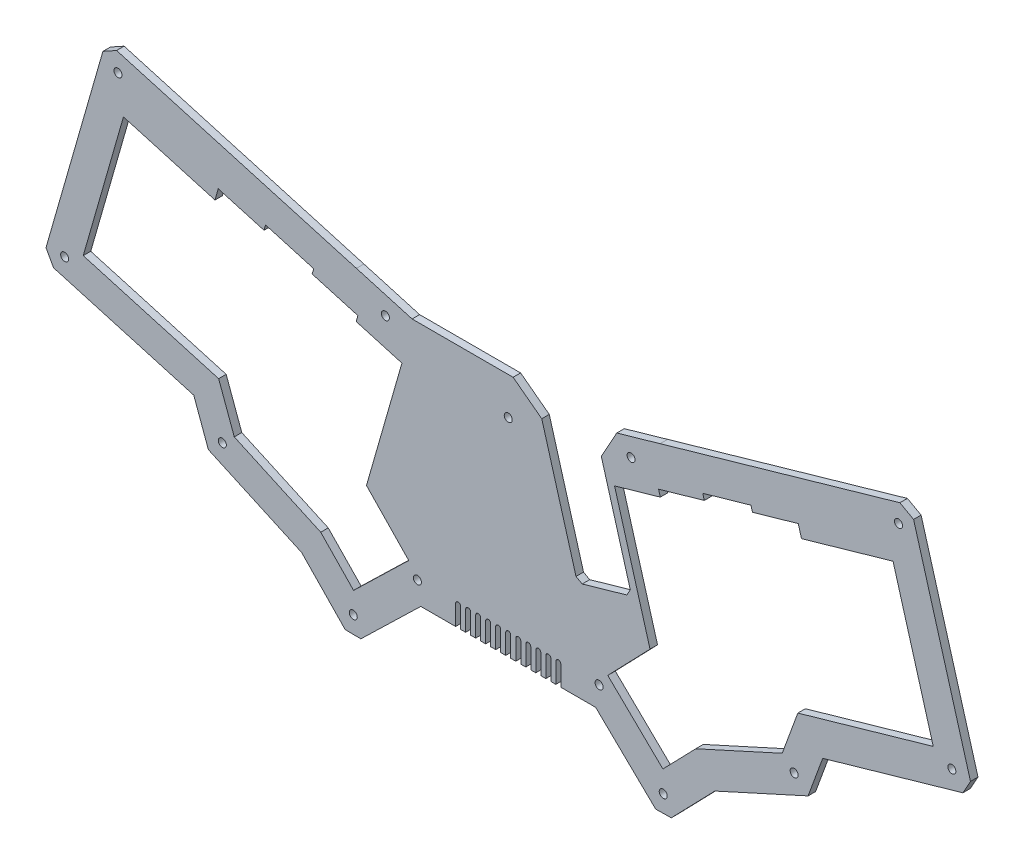
SolidWorks part; units mm, degrees
ref_plane "Plan de face" through (0, 0, 0) normal (0, 0, 1) x (1, 0, 0)
ref_plane "Plan de dessus" through (0, 0, 0) normal (0, 1, 0) x (1, 0, 0)
ref_plane "Plan de droite" through (0, 0, 0) normal (1, 0, 0) x (0, 0, -1)
sketch "Esquisse1" plane through (0, 0, 0) normal (0, 0, 1) x (1, 0, 0)
  line L0 (-121.6461, -32.0475) -> (-108.1875, -28.1884) construction
  line L1 (-108.1875, -28.1884) -> (-104.3283, -41.647) construction
  line L2 (-104.3283, -41.647) -> (-117.7869, -45.5062) construction
  line L3 (-117.7869, -45.5062) -> (-121.6461, -32.0475) construction
  line L4 (-100.1763, -37.9855) -> (-104.0355, -24.5269) construction
  line L5 (-104.0355, -24.5269) -> (-90.5769, -20.6677) construction
  line L6 (-90.5769, -20.6677) -> (-86.7177, -34.1263) construction
  line L7 (-86.7177, -34.1263) -> (-100.1763, -37.9855) construction
  line L8 (-82.5657, -30.4649) -> (-86.4249, -17.0063) construction
  line L9 (-86.4249, -17.0063) -> (-72.9663, -13.1471) construction
  line L10 (-72.9663, -13.1471) -> (-69.1071, -26.6057) construction
  line L11 (-69.1071, -26.6057) -> (-82.5657, -30.4649) construction
  line L12 (-63.6458, -27.5106) -> (-67.505, -14.0519) construction
  line L13 (-67.505, -14.0519) -> (-54.0463, -10.1927) construction
  line L14 (-54.0463, -10.1927) -> (-50.1872, -23.6514) construction
  line L15 (-50.1872, -23.6514) -> (-63.6458, -27.5106) construction
  line L16 (-44.0711, -26.8394) -> (-47.9303, -13.3808) construction
  line L17 (-47.9303, -13.3808) -> (-34.4717, -9.5216) construction
  line L18 (-34.4717, -9.5216) -> (-30.6125, -22.9802) construction
  line L19 (-30.6125, -22.9802) -> (-44.0711, -26.8394) construction
  line L20 (-25.8054, -21.6018) -> (-29.6646, -8.1432) construction
  line L21 (-29.6646, -8.1432) -> (-16.206, -4.284) construction
  line L22 (-16.206, -4.284) -> (-12.3468, -17.7426) construction
  line L23 (-12.3468, -17.7426) -> (-25.8054, -21.6018) construction
  line L24 (-116.4086, -50.3128) -> (-102.95, -46.4536) construction
  line L25 (-102.95, -46.4536) -> (-99.0908, -59.9122) construction
  line L26 (-99.0908, -59.9122) -> (-112.5494, -63.7714) construction
  line L27 (-112.5494, -63.7714) -> (-116.4086, -50.3128) construction
  line L28 (-98.798, -42.7922) -> (-85.3394, -38.933) construction
  line L29 (-85.3394, -38.933) -> (-81.4802, -52.3916) construction
  line L30 (-81.4802, -52.3916) -> (-94.9388, -56.2508) construction
  line L31 (-94.9388, -56.2508) -> (-98.798, -42.7922) construction
  line L32 (-81.1874, -35.2715) -> (-67.7288, -31.4123) construction
  line L33 (-67.7288, -31.4123) -> (-63.8696, -44.8709) construction
  line L34 (-63.8696, -44.8709) -> (-77.3282, -48.7301) construction
  line L35 (-77.3282, -48.7301) -> (-81.1874, -35.2715) construction
  line L36 (-62.2675, -32.3172) -> (-48.8089, -28.458) construction
  line L37 (-48.8089, -28.458) -> (-44.9497, -41.9166) construction
  line L38 (-44.9497, -41.9166) -> (-58.4083, -45.7758) construction
  line L39 (-58.4083, -45.7758) -> (-62.2675, -32.3172) construction
  line L40 (-42.6928, -31.646) -> (-29.2342, -27.7869) construction
  line L41 (-29.2342, -27.7869) -> (-25.375, -41.2455) construction
  line L42 (-25.375, -41.2455) -> (-38.8336, -45.1047) construction
  line L43 (-38.8336, -45.1047) -> (-42.6928, -31.646) construction
  line L44 (-24.4271, -26.4084) -> (-10.9685, -22.5492) construction
  line L45 (-10.9685, -22.5492) -> (-7.1093, -36.0078) construction
  line L46 (-7.1093, -36.0078) -> (-20.5679, -39.867) construction
  line L47 (-20.5679, -39.867) -> (-24.4271, -26.4084) construction
  line L48 (-19.1896, -44.6737) -> (-5.731, -40.8145) construction
  line L49 (-5.731, -40.8145) -> (-1.8718, -54.2731) construction
  line L50 (-1.8718, -54.2731) -> (-15.3304, -58.1323) construction
  line L51 (-15.3304, -58.1323) -> (-19.1896, -44.6737) construction
  line L52 (-37.4554, -49.9113) -> (-23.9967, -46.0521) construction
  line L53 (-23.9967, -46.0521) -> (-20.1376, -59.5107) construction
  line L54 (-20.1376, -59.5107) -> (-33.5962, -63.3699) construction
  line L55 (-33.5962, -63.3699) -> (-37.4554, -49.9113) construction
  line L56 (-57.03, -50.5825) -> (-43.5714, -46.7233) construction
  line L57 (-43.5714, -46.7233) -> (-39.7122, -60.1819) construction
  line L58 (-39.7122, -60.1819) -> (-53.1708, -64.0411) construction
  line L59 (-53.1708, -64.0411) -> (-57.03, -50.5825) construction
  line L60 (-75.9499, -53.5368) -> (-62.4913, -49.6776) construction
  line L61 (-62.4913, -49.6776) -> (-58.6321, -63.1362) construction
  line L62 (-58.6321, -63.1362) -> (-72.0908, -66.9954) construction
  line L63 (-72.0908, -66.9954) -> (-75.9499, -53.5368) construction
  line L64 (-93.5605, -61.0574) -> (-80.1019, -57.1982) construction
  line L65 (-80.1019, -57.1982) -> (-76.2427, -70.6569) construction
  line L66 (-76.2427, -70.6569) -> (-89.7013, -74.516) construction
  line L67 (-89.7013, -74.516) -> (-93.5605, -61.0574) construction
  line L68 (-111.1711, -68.5781) -> (-97.7125, -64.7189) construction
  line L69 (-97.7125, -64.7189) -> (-93.8533, -78.1775) construction
  line L70 (-93.8533, -78.1775) -> (-107.3119, -82.0367) construction
  line L71 (-107.3119, -82.0367) -> (-111.1711, -68.5781) construction
  line L72 (-79.0181, -77.3048) -> (-65.5595, -73.4456) construction
  line L73 (-65.5595, -73.4456) -> (-61.7003, -86.9042) construction
  line L74 (-61.7003, -86.9042) -> (-75.1589, -90.7634) construction
  line L75 (-75.1589, -90.7634) -> (-79.0181, -77.3048) construction
  line L76 (-99.4001, -88.1351) -> (-87.3916, -80.9362)
  line L77 (-87.3916, -80.9362) -> (-80.1927, -92.9448)
  line L78 (-80.1927, -92.9448) -> (-92.2012, -100.1436)
  line L79 (-92.2012, -100.1436) -> (-99.4001, -88.1351)
  line L80 (-120.0498, -100.4367) -> (-110.317, -90.3719)
  line L81 (-110.317, -90.3719) -> (-100.2522, -100.1047)
  line L82 (-100.2522, -100.1047) -> (-109.985, -110.1695)
  line L83 (-109.985, -110.1695) -> (-120.0498, -100.4367)
  line L86 (0.634, -55.7756) -> (-52.9527, -71.1413) construction
  line L89 (-59.2205, -88.2424) -> (-52.9527, -71.1413) construction
  line L96 (-93.4066, -103.0586) -> (-59.4637, -88.3612) construction
  line L97 (-105.418, -115.2057) -> (-93.9754, -103.3509) construction
  line L98 (-126.5332, -96.9919) -> (-107.5003, -115.385) construction
  line L99 (-167.7972, -50.1766) -> (-183.2082, -64.014) construction
  line L100 (-106.3822, -25.4572) -> (-123.6848, -30.4187) construction
  line L101 (-72.1178, -10.6906) -> (-88.4663, -15.3784) construction
  line L102 (-53.2337, -7.6163) -> (-70.5393, -12.5786) construction
  line L103 (-33.6604, -6.9452) -> (-50.9661, -11.9075) construction
  line L104 (-15.3965, -1.7081) -> (-31.745, -6.396) construction
  line L105 (0.5403, -55.2132) -> (-14.6896, -2.0999) construction
  line L106 (-16.199, -60.6113) -> (0.1495, -55.9235) construction
  line L107 (-52.7198, -71.0835) -> (-18.1144, -61.1606) construction
  line L108 (-59.1184, -88.0534) -> (-52.9674, -71.2752) construction
  line L109 (-183.2082, -64.014) -> (-173.1824, -64.9357) construction
  line L113 (-102.2678, -134.438) -> (-84.7238, -116.3191) construction
  line L114 (-84.7238, -116.3191) -> (-47.2969, -99.2981) construction
  line L115 (-47.2969, -99.2981) -> (-41.4917, -83.4594) construction
  line L116 (14.3812, -67.4381) -> (-41.4917, -83.4594) construction
  line L117 (17.8093, -61.2536) -> (-5.1371, 18.7701) construction
  line L122 (-11.3217, 22.1985) -> (-107.4545, -5.3614) construction
  line L129 (-167.7953, -27.6055) -> (-167.7953, -64.7189) construction
  line L130 (-242.0685, -103.8419) -> (-276.37, -88.2424) construction
  line L131 (-229.5108, -116.8112) -> (-242.0685, -103.8419) construction
  line L138 (-208.9328, -96.8551) -> (-229.5108, -116.8112) construction
  line L139 (-225.5107, -79.6567) -> (-208.9328, -96.8551) construction
  line L140 (-109.3352, -134.5492) -> (-102.2678, -134.438) construction
  line L142 (-5.1371, 18.7701) -> (-11.3217, 22.1985) construction
  line L143 (-211.4691, -30.6868) -> (-225.5107, -79.6567) construction
  line L147 (-114.18, -7.2899) -> (-107.4545, -5.3614) construction
  line L148 (-114.18, -7.2899) -> (-123.7936, -10.0465) construction
  line L154 (-4.3102, 15.8863) -> (-127.3606, -19.3904) construction
  line L155 (-131.531, -101.8802) -> (-105.9239, -126.7133) construction
  line L156 (-105.9239, -126.7133) -> (-89.4162, -109.6646) construction
  line L157 (-128.0696, -96.8789) -> (-106.0575, -118.2258)
  line L158 (-106.0575, -118.2258) -> (-92.9354, -104.6737)
  line L159 (-92.9354, -104.6737) -> (-58.4256, -88.9794)
  line L160 (-58.4256, -88.9794) -> (-52.1886, -71.9625)
  line L161 (1.8709, -56.4612) -> (-52.1886, -71.9625)
  line L162 (1.8709, -56.4612) -> (-14.1861, -0.4639)
  line L163 (-14.1861, -0.4639) -> (-50.7166, -10.9388)
  line L164 (-50.7166, -10.9388) -> (-52.026, -6.3725)
  line L165 (-52.026, -6.3725) -> (-70.2913, -11.61)
  line L166 (-70.2913, -11.61) -> (-70.911, -9.4488)
  line L167 (-70.911, -9.4488) -> (-90.1377, -14.9608)
  line L168 (-90.1377, -14.9608) -> (-89.5177, -17.1231)
  line L169 (-89.5177, -17.1231) -> (-107.783, -22.3606)
  line L170 (-107.783, -22.3606) -> (-107.0938, -24.7639)
  line L171 (-107.0938, -24.7639) -> (-125.3583, -30.0011)
  line L172 (-125.3583, -30.0011) -> (-111.2001, -79.378)
  line L173 (-111.2001, -79.378) -> (-127.3777, -96.1611)
  line L174 (-89.4162, -109.6646) -> (-53.6562, -93.4017) construction
  line L175 (-53.6562, -93.4017) -> (-47.6042, -76.8897) construction
  line L176 (9.2923, -60.5749) -> (-47.6042, -76.8897) construction
  line L177 (9.2923, -60.5749) -> (-12.0005, 13.6817) construction
  line L178 (-229.7336, -25.4495) -> (-211.4691, -30.6868) construction
  line L179 (-229.0444, -23.0462) -> (-229.7336, -25.4495) construction
  line L180 (-173.1824, -64.9357) -> (-167.7972, -60.1004) construction
  line L181 (-247.3097, -17.8087) -> (-229.0444, -23.0462) construction
  line L185 (17.8093, -61.2536) -> (14.3812, -67.4381) construction
  line L186 (-183.2987, -65.7677) -> (-173.2729, -66.6895) construction
  line L187 (-173.2729, -66.6895) -> (-167.8052, -74.7882) construction
  line L190 (-246.6897, -15.6465) -> (-247.3097, -17.8087) construction
  line L191 (-263.9939, -10.6857) -> (-246.6897, -15.6465) construction
  line L192 (-264.6136, -12.8469) -> (-263.9939, -10.6857) construction
  line L193 (-282.8789, -7.6094) -> (-264.6136, -12.8469) construction
  line L194 (-284.1883, -12.1757) -> (-282.8789, -7.6094) construction
  line L195 (-320.7188, -1.7008) -> (-284.1883, -12.1757) construction
  line L196 (-336.2245, -55.7756) -> (-320.7188, -1.7008) construction
  line L197 (-183.2987, -65.7677) -> (-167.8052, -88.0782) construction
  line L198 (-181.8414, -71.5322) -> (-174.8684, -81.0171) construction
  line L199 (-174.8684, -81.0171) -> (-178.3549, -83.9622) construction
  line L200 (-344.8828, -60.5749) -> (-323.5901, 13.6817) construction
  line L201 (-344.8828, -60.5749) -> (-287.9863, -76.8897) construction
  line L202 (-281.9343, -93.4017) -> (-287.9863, -76.8897) construction
  line L203 (-246.1743, -109.6646) -> (-281.9343, -93.4017) construction
  line L204 (-224.3904, -79.378) -> (-208.2128, -96.1611)
  line L205 (-210.2322, -30.0011) -> (-224.3904, -79.378)
  line L206 (-228.4967, -24.7639) -> (-210.2322, -30.0011)
  line L207 (-227.8075, -22.3606) -> (-228.4967, -24.7639)
  line L208 (-246.0728, -17.1231) -> (-227.8075, -22.3606)
  line L209 (-245.4528, -14.9608) -> (-246.0728, -17.1231)
  line L210 (-264.6796, -9.4488) -> (-245.4528, -14.9608)
  line L211 (-265.2993, -11.61) -> (-264.6796, -9.4488)
  line L212 (-283.5645, -6.3725) -> (-265.2993, -11.61)
  line L213 (-284.8739, -10.9388) -> (-283.5645, -6.3725)
  line L217 (0.634, -55.7756) -> (-14.8717, -1.7008) construction
  line L220 (-14.8717, -1.7008) -> (-51.4022, -12.1757) construction
  line L221 (-51.4022, -12.1757) -> (-52.7116, -7.6094) construction
  line L222 (-52.7116, -7.6094) -> (-70.9769, -12.8469) construction
  line L223 (-70.9769, -12.8469) -> (-71.5966, -10.6857) construction
  line L224 (-71.5966, -10.6857) -> (-88.9008, -15.6465) construction
  line L225 (-88.9008, -15.6465) -> (-88.2808, -17.8087) construction
  line L226 (-88.2808, -17.8087) -> (-106.5461, -23.0462) construction
  line L227 (-106.5461, -23.0462) -> (-105.8569, -25.4495) construction
  line L228 (-105.8569, -25.4495) -> (-124.1214, -30.6868) construction
  line L231 (-124.1214, -30.6868) -> (-110.0799, -79.6567) construction
  line L232 (-110.0799, -79.6567) -> (-126.6577, -96.8551) construction
  line L233 (-126.6577, -96.8551) -> (-106.0797, -116.8112) construction
  line L234 (-106.0797, -116.8112) -> (-93.522, -103.8419) construction
  line L235 (-93.522, -103.8419) -> (-59.2205, -88.2424) construction
  line L236 (-321.4044, -0.4639) -> (-284.8739, -10.9388)
  line L237 (-337.4614, -56.4612) -> (-321.4044, -0.4639)
  line L238 (-337.4614, -56.4612) -> (-283.4019, -71.9625)
  line L239 (-277.1649, -88.9794) -> (-283.4019, -71.9625)
  line L240 (-242.6551, -104.6737) -> (-277.1649, -88.9794)
  line L241 (-229.5331, -118.2258) -> (-242.6551, -104.6737)
  line L242 (-208.2366, -97.573) -> (-229.5331, -118.2258)
  line L243 (-229.6666, -126.7133) -> (-246.1743, -109.6646) construction
  line L244 (-204.0596, -101.8802) -> (-229.6666, -126.7133) construction
  line L245 (-331.2803, 15.8863) -> (-208.2299, -19.3904) construction
  line L246 (-178.3549, -83.9622) -> (-185.8788, -75.0552) construction
  line L247 (-185.8788, -75.0552) -> (-181.8414, -71.5322) construction
  line L248 (-176.7625, -46.6332) -> (-185.5498, -54.5291) construction
  line L249 (-185.5498, -54.5291) -> (-181.1562, -59.4188) construction
  line L250 (-181.1562, -59.4188) -> (-172.3689, -51.5229) construction
  line L251 (-276.4721, -88.0534) -> (-282.6232, -71.2752) construction
  line L252 (-282.8707, -71.0835) -> (-317.4761, -61.1606) construction
  line L253 (-319.3915, -60.6113) -> (-335.74, -55.9235) construction
  line L254 (-336.1309, -55.2132) -> (-320.9009, -2.0999) construction
  line L255 (-320.194, -1.7081) -> (-303.8455, -6.396) construction
  line L256 (-301.9301, -6.9452) -> (-284.6245, -11.9075) construction
  line L257 (-282.3568, -7.6163) -> (-265.0512, -12.5786) construction
  line L258 (-263.4727, -10.6906) -> (-247.1242, -15.3784) construction
  line L259 (-229.2083, -25.4572) -> (-211.9057, -30.4187) construction
  line L260 (-172.3689, -51.5229) -> (-176.7625, -46.6332) construction
  line L261 (-209.0573, -96.9919) -> (-228.0902, -115.385) construction
  line L262 (-230.1725, -115.2057) -> (-241.6151, -103.3509) construction
  line L263 (-242.1839, -103.0586) -> (-276.1268, -88.3612) construction
  line L264 (-276.37, -88.2424) -> (-282.6379, -71.1413) construction
  line L265 (-336.2245, -55.7756) -> (-282.6379, -71.1413) construction
  line L268 (-353.3998, -61.2536) -> (-349.9717, -67.4381) construction
  line L274 (-221.4105, -7.2899) -> (-206.0252, -11.7015) construction
  line L275 (-221.4105, -7.2899) -> (-228.136, -5.3614) construction
  line L276 (-330.4534, 18.7701) -> (-324.2688, 22.1985) construction
  line L277 (-226.2553, -134.5492) -> (-233.3227, -134.438) construction
  line L281 (-324.2688, 22.1985) -> (-228.136, -5.3614) construction
  line L282 (-353.3998, -61.2536) -> (-330.4534, 18.7701) construction
  line L283 (-349.9717, -67.4381) -> (-294.0988, -83.4594) construction
  line L284 (-288.2936, -99.2981) -> (-294.0988, -83.4594) construction
  line L285 (-250.8667, -116.3191) -> (-288.2936, -99.2981) construction
  line L286 (-233.3227, -134.438) -> (-250.8667, -116.3191) construction
  line L288 (-225.6055, -110.1695) -> (-215.5407, -100.4367) construction
  line L289 (-235.3383, -100.1047) -> (-225.6055, -110.1695) construction
  line L290 (-225.2735, -90.3719) -> (-235.3383, -100.1047) construction
  line L291 (-215.5407, -100.4367) -> (-225.2735, -90.3719) construction
  line L292 (-243.3893, -100.1436) -> (-236.1904, -88.1351) construction
  line L293 (-255.3978, -92.9448) -> (-243.3893, -100.1436) construction
  line L294 (-248.1989, -80.9362) -> (-255.3978, -92.9448) construction
  line L295 (-236.1904, -88.1351) -> (-248.1989, -80.9362) construction
  line L296 (-260.4316, -90.7634) -> (-256.5724, -77.3048) construction
  line L297 (-273.8902, -86.9042) -> (-260.4316, -90.7634) construction
  line L298 (-270.031, -73.4456) -> (-273.8902, -86.9042) construction
  line L299 (-256.5724, -77.3048) -> (-270.031, -73.4456) construction
  line L300 (-228.2786, -82.0367) -> (-224.4194, -68.5781) construction
  line L301 (-241.7372, -78.1775) -> (-228.2786, -82.0367) construction
  line L302 (-237.878, -64.7189) -> (-241.7372, -78.1775) construction
  line L303 (-224.4194, -68.5781) -> (-237.878, -64.7189) construction
  line L304 (-245.8892, -74.516) -> (-242.03, -61.0574) construction
  line L305 (-259.3478, -70.6569) -> (-245.8892, -74.516) construction
  line L306 (-255.4886, -57.1982) -> (-259.3478, -70.6569) construction
  line L307 (-242.03, -61.0574) -> (-255.4886, -57.1982) construction
  line L308 (-263.4998, -66.9954) -> (-259.6406, -53.5368) construction
  line L309 (-276.9584, -63.1362) -> (-263.4998, -66.9954) construction
  line L310 (-273.0992, -49.6776) -> (-276.9584, -63.1362) construction
  line L311 (-259.6406, -53.5368) -> (-273.0992, -49.6776) construction
  line L312 (-282.4197, -64.0411) -> (-278.5605, -50.5825) construction
  line L313 (-295.8783, -60.1819) -> (-282.4197, -64.0411) construction
  line L314 (-292.0191, -46.7233) -> (-295.8783, -60.1819) construction
  line L315 (-278.5605, -50.5825) -> (-292.0191, -46.7233) construction
  line L316 (-301.9944, -63.3699) -> (-298.1352, -49.9113) construction
  line L317 (-315.453, -59.5107) -> (-301.9944, -63.3699) construction
  line L318 (-311.5938, -46.0521) -> (-315.453, -59.5107) construction
  line L319 (-298.1352, -49.9113) -> (-311.5938, -46.0521) construction
  line L320 (-320.2601, -58.1323) -> (-316.4009, -44.6737) construction
  line L321 (-333.7187, -54.2731) -> (-320.2601, -58.1323) construction
  line L322 (-329.8595, -40.8145) -> (-333.7187, -54.2731) construction
  line L323 (-316.4009, -44.6737) -> (-329.8595, -40.8145) construction
  line L324 (-315.0226, -39.867) -> (-311.1634, -26.4084) construction
  line L325 (-328.4812, -36.0078) -> (-315.0226, -39.867) construction
  line L326 (-324.622, -22.5492) -> (-328.4812, -36.0078) construction
  line L327 (-311.1634, -26.4084) -> (-324.622, -22.5492) construction
  line L328 (-296.7569, -45.1047) -> (-292.8977, -31.646) construction
  line L329 (-310.2155, -41.2455) -> (-296.7569, -45.1047) construction
  line L330 (-306.3563, -27.7869) -> (-310.2155, -41.2455) construction
  line L331 (-292.8977, -31.646) -> (-306.3563, -27.7869) construction
  line L332 (-277.1822, -45.7758) -> (-273.323, -32.3172) construction
  line L333 (-290.6408, -41.9166) -> (-277.1822, -45.7758) construction
  line L334 (-286.7817, -28.458) -> (-290.6408, -41.9166) construction
  line L335 (-273.323, -32.3172) -> (-286.7817, -28.458) construction
  line L336 (-258.2623, -48.7301) -> (-254.4031, -35.2715) construction
  line L337 (-271.7209, -44.8709) -> (-258.2623, -48.7301) construction
  line L338 (-267.8617, -31.4123) -> (-271.7209, -44.8709) construction
  line L339 (-254.4031, -35.2715) -> (-267.8617, -31.4123) construction
  line L340 (-240.6517, -56.2508) -> (-236.7925, -42.7922) construction
  line L341 (-254.1103, -52.3916) -> (-240.6517, -56.2508) construction
  line L342 (-250.2511, -38.933) -> (-254.1103, -52.3916) construction
  line L343 (-236.7925, -42.7922) -> (-250.2511, -38.933) construction
  line L344 (-223.0411, -63.7714) -> (-219.1819, -50.3128) construction
  line L345 (-236.4997, -59.9122) -> (-223.0411, -63.7714) construction
  line L346 (-232.6405, -46.4536) -> (-236.4997, -59.9122) construction
  line L347 (-219.1819, -50.3128) -> (-232.6405, -46.4536) construction
  line L348 (-323.2438, -17.7426) -> (-309.7851, -21.6018) construction
  line L349 (-319.3846, -4.284) -> (-323.2438, -17.7426) construction
  line L350 (-305.926, -8.1432) -> (-319.3846, -4.284) construction
  line L351 (-309.7851, -21.6018) -> (-305.926, -8.1432) construction
  line L352 (-304.978, -22.9802) -> (-291.5194, -26.8394) construction
  line L353 (-301.1188, -9.5216) -> (-304.978, -22.9802) construction
  line L354 (-287.6602, -13.3808) -> (-301.1188, -9.5216) construction
  line L355 (-291.5194, -26.8394) -> (-287.6602, -13.3808) construction
  line L356 (-285.4034, -23.6514) -> (-271.9448, -27.5106) construction
  line L357 (-281.5442, -10.1927) -> (-285.4034, -23.6514) construction
  line L358 (-268.0856, -14.0519) -> (-281.5442, -10.1927) construction
  line L359 (-271.9448, -27.5106) -> (-268.0856, -14.0519) construction
  line L360 (-266.4834, -26.6057) -> (-253.0248, -30.4649) construction
  line L361 (-262.6242, -13.1471) -> (-266.4834, -26.6057) construction
  line L362 (-249.1656, -17.0063) -> (-262.6242, -13.1471) construction
  line L363 (-253.0248, -30.4649) -> (-249.1656, -17.0063) construction
  line L364 (-248.8728, -34.1263) -> (-235.4142, -37.9855) construction
  line L365 (-245.0136, -20.6677) -> (-248.8728, -34.1263) construction
  line L366 (-231.555, -24.5269) -> (-245.0136, -20.6677) construction
  line L367 (-235.4142, -37.9855) -> (-231.555, -24.5269) construction
  line L368 (-217.8036, -45.5062) -> (-213.9444, -32.0475) construction
  line L369 (-231.2622, -41.647) -> (-217.8036, -45.5062) construction
  line L370 (-227.4031, -28.1884) -> (-231.2622, -41.647) construction
  line L371 (-213.9444, -32.0475) -> (-227.4031, -28.1884) construction
  line L372 (-226.2553, -134.5492) -> (-194.0347, -103.3509) construction
  line L373 (-109.3352, -134.5492) -> (-141.5559, -103.3509) construction
  line L374 (-141.5559, -103.3509) -> (-194.0347, -103.3509) construction
  line L375 (-167.7972, -50.1766) -> (-152.3861, -64.014) construction
  line L376 (-162.4119, -64.9357) -> (-167.7972, -60.1004) construction
  line L377 (-162.3376, -66.6895) -> (-167.8052, -74.7882) construction
  line L378 (-152.3118, -65.7677) -> (-167.8052, -88.0782) construction
  line L379 (-163.2254, -51.5229) -> (-158.8318, -46.6332) construction
  line L380 (-154.4381, -59.4188) -> (-163.2254, -51.5229) construction
  line L381 (-150.0445, -54.5291) -> (-154.4381, -59.4188) construction
  line L382 (-158.8318, -46.6332) -> (-150.0445, -54.5291) construction
  line L383 (-149.7316, -75.0552) -> (-153.7691, -71.5322) construction
  line L384 (-157.2555, -83.9622) -> (-149.7316, -75.0552) construction
  line L385 (-160.742, -81.0171) -> (-157.2555, -83.9622) construction
  line L386 (-153.7691, -71.5322) -> (-160.742, -81.0171) construction
  line L387 (-152.3118, -65.7677) -> (-162.3376, -66.6895) construction
  line L388 (-152.3861, -64.014) -> (-162.4119, -64.9357) construction
  line L389 (-206.0252, -11.7015) -> (-129.5654, -11.7015) construction
  line L390 (-119.0708, -62.7964) -> (-130.6498, -22.4155)
  line L391 (-123.5545, -47.16) -> (-127.4136, -33.7014) construction
  line L392 (-120.442, -65.2702) -> (-138.2688, -70.3819)
  line L393 (-140.7426, -69.0107) -> (-154.4194, -21.3141)
  line L394 (-167.1758, -11.7015) -> (-206.0252, -11.7015) construction
  line L395 (-154.4194, -21.3141) -> (-167.1758, -11.7015) construction
  line L396 (-123.7936, -10.0465) -> (-130.6498, -22.4155) construction
  line L397 (-138.2688, -70.3819) -> (-140.7426, -69.0107)
  line L398 (-119.0708, -62.7964) -> (-120.442, -65.2702)
  line L399 (-129.5654, -11.7015) -> (-123.7936, -10.0465) construction
  line L400 (-165.8487, -12.7015) -> (-206.1657, -12.7015)
  line L401 (-221.6861, -8.2511) -> (-206.1657, -12.7015)
  line L402 (-221.6861, -8.2511) -> (-228.4116, -6.3226)
  line L403 (-324.1462, 21.1231) -> (-228.4116, -6.3226)
  line L404 (-329.6063, 18.0963) -> (-324.1462, 21.1231)
  line L405 (-352.3244, -61.1311) -> (-329.6063, 18.0963)
  line L406 (-352.3244, -61.1311) -> (-349.2979, -66.591)
  line L407 (-349.2979, -66.591) -> (-293.3347, -82.6382)
  line L408 (-287.4987, -98.561) -> (-293.3347, -82.6382)
  line L409 (-250.2802, -115.4872) -> (-287.4987, -98.561)
  line L410 (-232.8926, -133.4446) -> (-250.2802, -115.4872)
  line L411 (-226.6535, -133.5428) -> (-232.8926, -133.4446)
  line L412 (-226.6535, -133.5428) -> (-202.7016, -110.3509)
  line L413 (-141.1511, -102.3509) -> (-194.4395, -102.3509) construction
  line L414 (-108.937, -133.5428) -> (-132.8889, -110.3509)
  line L415 (-108.937, -133.5428) -> (-102.6979, -133.4446)
  line L416 (-102.6979, -133.4446) -> (-85.3104, -115.4872)
  line L417 (-85.3104, -115.4872) -> (-48.0918, -98.561)
  line L418 (-48.0918, -98.561) -> (-42.2558, -82.6382)
  line L419 (13.7074, -66.591) -> (-42.2558, -82.6382)
  line L420 (16.7339, -61.1311) -> (13.7074, -66.591)
  line L421 (16.7339, -61.1311) -> (-5.9842, 18.0963)
  line L422 (-5.9842, 18.0963) -> (-11.4443, 21.1231)
  line L423 (-11.4443, 21.1231) -> (-107.1789, -6.3226)
  line L424 (-113.9044, -8.2511) -> (-107.1789, -6.3226)
  line L425 (-113.9044, -8.2511) -> (-124.4792, -11.2834)
  line L426 (-167.1758, -12.7015) -> (-206.1657, -12.7015) construction
  line L427 (-113.9044, -8.2511) -> (-123.5179, -11.0078) construction
  line L428 (-165.8487, -12.7015) -> (-154.4194, -21.3141)
  line L429 (-130.6498, -22.4155) -> (-124.4792, -11.2834)
  line L430 (-208.2366, -97.573) -> (-207.4919, -96.8551)
  line L431 (-207.4919, -96.8551) -> (-208.2128, -96.1611)
  line L432 (-127.3777, -96.1611) -> (-128.0696, -96.8789)
  line L433 (-132.8889, -110.3509) -> (-202.7016, -110.3509)
  line L434 (-141.1511, -110.3509) -> (-194.4395, -110.3509) construction
  line L436 (-226.6535, -133.5428) -> (-194.4395, -102.3509) construction
  line L437 (-108.937, -133.5428) -> (-141.1511, -102.3509) construction
  circle A2 centre (-12.0005, 13.6817) radius 1.6
  circle A3 centre (-12.0005, 13.6817) radius 3 construction
  circle A4 centre (-118.7579, -16.9241) radius 1.6
  circle A5 centre (9.2923, -60.5749) radius 1.6
  circle A6 centre (-53.6562, -93.4017) radius 1.6
  circle A7 centre (-105.9239, -126.7133) radius 1.6
  circle A8 centre (-131.531, -101.8802) radius 1.6
  circle A10 centre (-147.4897, -45.973) radius 1.6 construction
  circle A11 centre (-323.5901, 13.6817) radius 3 construction
  circle A12 centre (-188.1008, -45.973) radius 1.6 construction
  circle A14 centre (-204.0596, -101.8802) radius 1.6
  circle A15 centre (-229.6666, -126.7133) radius 1.6
  circle A16 centre (-281.9343, -93.4017) radius 1.6
  circle A17 centre (-344.8828, -60.5749) radius 1.6
  circle A18 centre (-216.8326, -16.9241) radius 1.6
  circle A19 centre (-323.5901, 13.6817) radius 1.6
  circle A20 centre (-167.7953, -27.6055) radius 1.6
  point P138 (-167.7953, -27.6055)
  point P139 (-6.5153, 23.5764)
  point P150 (-169.1046, -23.0392)
  point P200 (19.1875, -66.0599)
  point P203 (-141.5228, -71.3355)
  point P204 (-141.5228, 1.5705)
  point P263 (-133.4062, -12.8029)
  point P264 (-118.5195, -64.7189)
  point P283 (-140.1914, -70.9332)
  point P284 (-157.1758, -11.7015)
  point P405 (-354.778, -66.0599)
  point P406 (-329.0752, 23.5764)
  dimension "D3" = 3.2
  dimension "D4" = 6
  dimension "D6" = 3.2
  dimension "D7" = 3.2
  dimension "D8" = 3.2
  dimension "D9" = 3.2
  dimension "D10" = 3.2
  dimension "D16" = 3.2
  dimension "D2" = 6
  dimension "D5" = 1
  dimension "D11" = 8
extrude "Boss.-Extru.1" add sketch "Esquisse1" along normal blind 3 contours L429 L390 L398 L392 L397 L393 L428 L400 L401 L402 L403 L404 L405 L406 L407 L408 L409 L410 L411 L412 L413 L414 L415 L416 L417 L418 L419 L420 L421 L422 L423 L424 L425 A19 A17 A15 L431 L430 L242 L241 L240 L239 L238 L237 L236 L213 L212
sketch "Esquisse2" plane through (0, 0, 3) normal (0, 0, 1) x (1, 0, 0)
  line L0 (-167.7953, -110.3509) -> (-167.7953, -102.3509) construction
  line L1 (-132.8889, -110.3509) -> (-202.7016, -110.3509) construction
  line L2 (-168.7953, -110.3509) -> (-168.7953, -102.3509)
  line L3 (-166.7953, -110.3509) -> (-166.7953, -102.3509)
  line L4 (-163.7953, -110.3509) -> (-163.7953, -102.3509) construction
  line L5 (-164.7953, -110.3509) -> (-164.7953, -102.3509)
  line L6 (-162.7953, -110.3509) -> (-162.7953, -102.3509)
  line L7 (-159.7953, -110.3509) -> (-159.7953, -102.3509) construction
  line L8 (-160.7953, -110.3509) -> (-160.7953, -102.3509)
  line L9 (-158.7953, -110.3509) -> (-158.7953, -102.3509)
  line L10 (-155.7953, -110.3509) -> (-155.7953, -102.3509) construction
  line L11 (-156.7953, -110.3509) -> (-156.7953, -102.3509)
  line L12 (-154.7953, -110.3509) -> (-154.7953, -102.3509)
  line L13 (-151.7953, -110.3509) -> (-151.7953, -102.3509) construction
  line L14 (-152.7953, -110.3509) -> (-152.7953, -102.3509)
  line L15 (-150.7953, -110.3509) -> (-150.7953, -102.3509)
  line L16 (-147.7953, -110.3509) -> (-147.7953, -102.3509) construction
  line L17 (-148.7953, -110.3509) -> (-148.7953, -102.3509)
  line L18 (-146.7953, -110.3509) -> (-146.7953, -102.3509)
  line L19 (-171.7953, -110.3509) -> (-171.7953, -102.3509) construction
  line L20 (-172.7953, -110.3509) -> (-172.7953, -102.3509)
  line L21 (-170.7953, -110.3509) -> (-170.7953, -102.3509)
  line L22 (-175.7953, -110.3509) -> (-175.7953, -102.3509) construction
  line L23 (-176.7953, -110.3509) -> (-176.7953, -102.3509)
  line L24 (-174.7953, -110.3509) -> (-174.7953, -102.3509)
  line L25 (-179.7953, -110.3509) -> (-179.7953, -102.3509) construction
  line L26 (-180.7953, -110.3509) -> (-180.7953, -102.3509)
  line L27 (-178.7953, -110.3509) -> (-178.7953, -102.3509)
  line L28 (-183.7953, -110.3509) -> (-183.7953, -102.3509) construction
  line L29 (-184.7953, -110.3509) -> (-184.7953, -102.3509)
  line L30 (-182.7953, -110.3509) -> (-182.7953, -102.3509)
  line L31 (-187.7953, -110.3509) -> (-187.7953, -102.3509) construction
  line L32 (-188.7953, -110.3509) -> (-188.7953, -102.3509)
  line L33 (-186.7953, -110.3509) -> (-186.7953, -102.3509)
  arc A0 (-168.7953, -110.3509) -> (-166.7953, -110.3509) centre (-167.7953, -110.3509) ccw
  arc A1 (-166.7953, -102.3509) -> (-168.7953, -102.3509) centre (-167.7953, -102.3509) ccw
  arc A2 (-164.7953, -110.3509) -> (-162.7953, -110.3509) centre (-163.7953, -110.3509) ccw
  arc A3 (-162.7953, -102.3509) -> (-164.7953, -102.3509) centre (-163.7953, -102.3509) ccw
  arc A4 (-160.7953, -110.3509) -> (-158.7953, -110.3509) centre (-159.7953, -110.3509) ccw
  arc A5 (-158.7953, -102.3509) -> (-160.7953, -102.3509) centre (-159.7953, -102.3509) ccw
  arc A6 (-156.7953, -110.3509) -> (-154.7953, -110.3509) centre (-155.7953, -110.3509) ccw
  arc A7 (-154.7953, -102.3509) -> (-156.7953, -102.3509) centre (-155.7953, -102.3509) ccw
  arc A8 (-152.7953, -110.3509) -> (-150.7953, -110.3509) centre (-151.7953, -110.3509) ccw
  arc A9 (-150.7953, -102.3509) -> (-152.7953, -102.3509) centre (-151.7953, -102.3509) ccw
  arc A10 (-148.7953, -110.3509) -> (-146.7953, -110.3509) centre (-147.7953, -110.3509) ccw
  arc A11 (-146.7953, -102.3509) -> (-148.7953, -102.3509) centre (-147.7953, -102.3509) ccw
  arc A12 (-172.7953, -110.3509) -> (-170.7953, -110.3509) centre (-171.7953, -110.3509) ccw
  arc A13 (-170.7953, -102.3509) -> (-172.7953, -102.3509) centre (-171.7953, -102.3509) ccw
  arc A14 (-176.7953, -110.3509) -> (-174.7953, -110.3509) centre (-175.7953, -110.3509) ccw
  arc A15 (-174.7953, -102.3509) -> (-176.7953, -102.3509) centre (-175.7953, -102.3509) ccw
  arc A16 (-180.7953, -110.3509) -> (-178.7953, -110.3509) centre (-179.7953, -110.3509) ccw
  arc A17 (-178.7953, -102.3509) -> (-180.7953, -102.3509) centre (-179.7953, -102.3509) ccw
  arc A18 (-184.7953, -110.3509) -> (-182.7953, -110.3509) centre (-183.7953, -110.3509) ccw
  arc A19 (-182.7953, -102.3509) -> (-184.7953, -102.3509) centre (-183.7953, -102.3509) ccw
  arc A20 (-188.7953, -110.3509) -> (-186.7953, -110.3509) centre (-187.7953, -110.3509) ccw
  arc A21 (-186.7953, -102.3509) -> (-188.7953, -102.3509) centre (-187.7953, -102.3509) ccw
  point P4 (-167.7953, -106.3509)
  point P13 (-163.7953, -106.3509)
  point P20 (-159.7953, -106.3509)
  point P27 (-155.7953, -106.3509)
  point P34 (-151.7953, -106.3509)
  point P41 (-147.7953, -106.3509)
  point P47 (-171.7953, -106.3509)
  point P54 (-175.7953, -106.3509)
  point P61 (-179.7953, -106.3509)
  point P68 (-183.7953, -106.3509)
  point P75 (-187.7953, -106.3509)
  dimension "D1" = 6
  dimension "D2" = 6
extrude "Enlèv. mat.-Extru.1" cut sketch "Esquisse2" against normal blind 10
